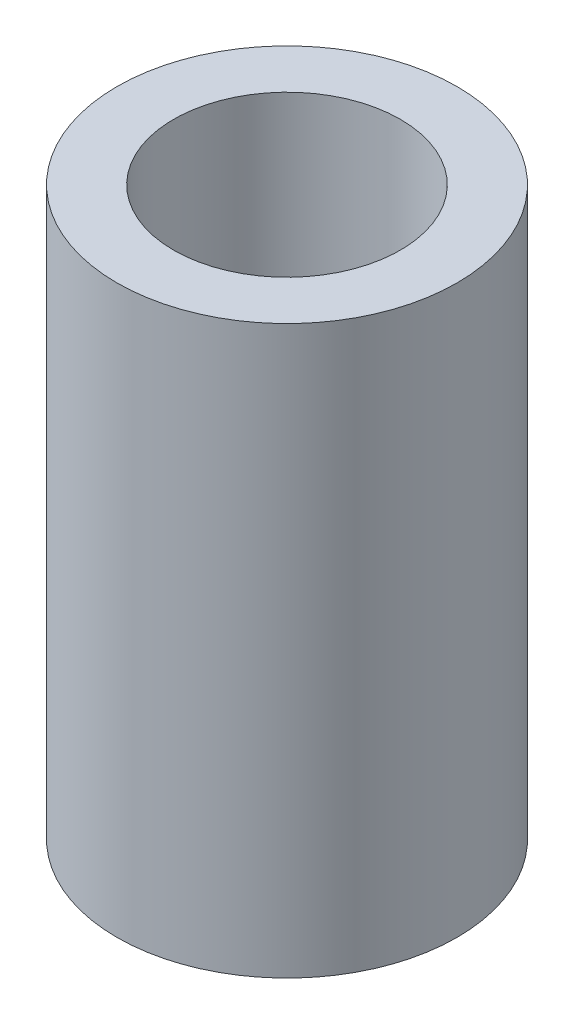
SolidWorks part; units mm, degrees
ref_plane "Ön Düzlem" through (0, 0, 0) normal (0, 0, 1) x (1, 0, 0)
ref_plane "Üst Düzlem" through (0, 0, 0) normal (0, 1, 0) x (1, 0, 0)
ref_plane "Sağ Düzlem" through (0, 0, 0) normal (1, 0, 0) x (0, 0, -1)
sketch "Sketch1" plane through (0, 0, 0) normal (0, 0, 1) x (1, 0, 0)
  line L0 (0, 0) -> (23797.3324, 0) construction
  line L1 (0, 0) -> (0, -23797.3324) construction
  line L2 (110, 0) -> (110, 37) construction
  line L3 (55, 0) -> (55, -18) construction
  line L4 (55, 0) -> (55, 53) construction
  line L5 (0, 0) -> (55, 53) construction
  line L6 (55, 53) -> (110, 37) construction
  line L7 (110, 37) -> (55, -18) construction
  line L8 (55, -18) -> (0, 0) construction
  circle A0 centre (0, 0) radius 3.7282
  circle A1 centre (55, -18) radius 3.8922
  dimension "D1" = 55
  dimension "D2" = 53
  dimension "D4" = 18
  dimension "D5" = 110
  dimension "D6" = 37
ref_plane "Front Hole Plane" through (110, 37, 0) normal (0, 1, 0) x (1, 0, 0)
sketch "Sketch2" plane through (110, 37, 0) normal (0, 1, 0) x (1, 0, 0)
  line L0 (0, 0) -> (-55, 0) construction
  line L1 (-200110, 0) -> (223687.3324, 0) construction
  circle A0 centre (0, 0) radius 3
  dimension "D1" = 6
ref_plane "Seat Plane" through (55, 53, 0) normal (0, 1, 0) x (1, 0, 0)
sketch "Sketch3" plane through (55, 53, 0) normal (0, 1, 0) x (1, 0, 0)
  line L0 (0, 0) -> (-55, 0) construction
  line L1 (55, 0) -> (0, 0) construction
  circle A0 centre (0, 0) radius 6.2361
extrude "Boss-Extrude1" add sketch "Sketch2" along normal blind 10
sketch "Sketch4" plane through (0, 47, 0) normal (0, 1, 0) x (1, 0, 0)
  line L0 (110, 0) -> (55, 0) construction
  line L1 (55, 0) -> (110, 0) construction
  circle A0 centre (110, 0) radius 2
  dimension "D1" = 4
extrude "Cut-Extrude1" cut sketch "Sketch4" against normal through all
sketch "Sketch5" plane through (0, 0, 0) normal (0, 0, 1) x (1, 0, 0)
  line L0 (107, 37) -> (65.9462, -5.1959)
equation "\"Front Hole\"= 6mm"
equation "\"Front Hole Length\"= 10mm"
equation "\"thickkk\" = 10mm"
equation "\"thickk\"= 10mm"
equation "\"thick\"= 10mm"
equation "\"D1@Sketch2\"=\"Front Hole\""
equation "\"D1@Boss-Extrude1\"=\"Front Hole Length\""
